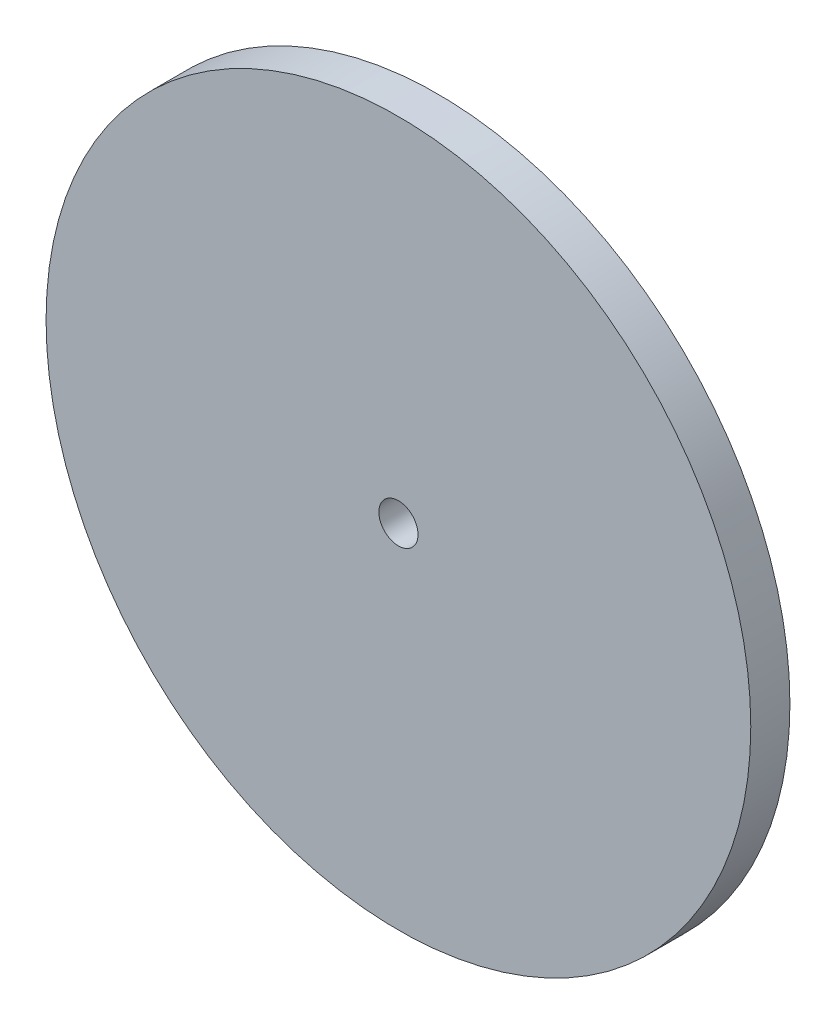
SolidWorks part; units mm, degrees
material "AISI 1020"
ref_plane "Plano frontal" through (0, 0, 0) normal (0, 0, 1) x (1, 0, 0)
ref_plane "Plano superior" through (0, 0, 0) normal (0, 1, 0) x (1, 0, 0)
ref_plane "Plano direito" through (0, 0, 0) normal (1, 0, 0) x (0, 0, -1)
sketch "Esboço1" plane through (0, 0, 0) normal (0, 0, 1) x (1, 0, 0)
  circle A0 centre (0, 0) radius 45
  circle A1 centre (0, 0) radius 2.5
  dimension "D1" = 5
  dimension "D2" = 90
extrude "Extrusão1" add sketch "Esboço1" along normal blind 5
